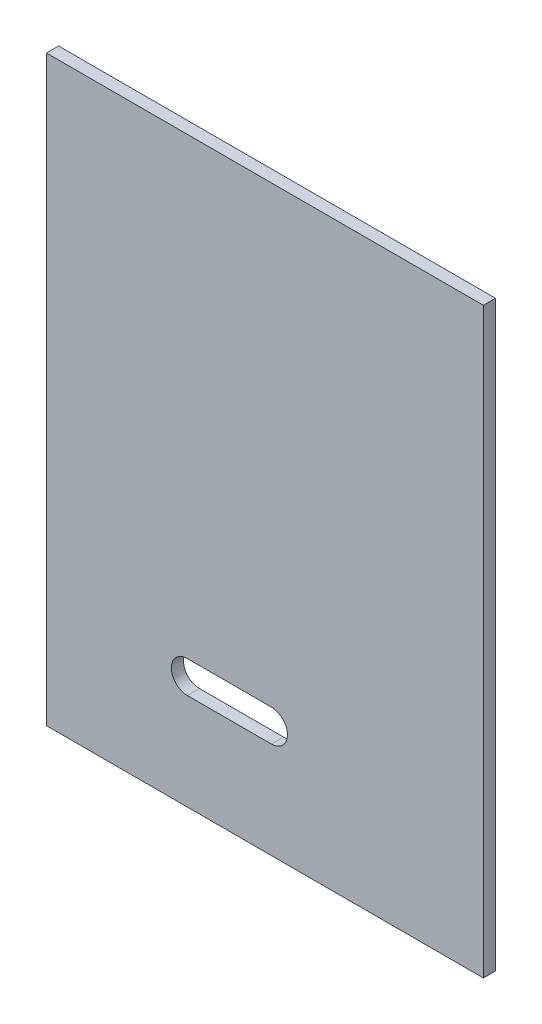
SolidWorks part; units mm, degrees
ref_plane "Front Plane" through (0, 0, 0) normal (0, 0, 1) x (1, 0, 0)
ref_plane "Top Plane" through (0, 0, 0) normal (0, 1, 0) x (1, 0, 0)
ref_plane "Right Plane" through (0, 0, 0) normal (1, 0, 0) x (0, 0, -1)
sketch "Sketch1" plane through (0, 0, 0) normal (0, 0, 1) x (1, 0, 0)
  line L0 (228.6, 0) -> (0, 0)
  line L1 (0, 0) -> (0, 304.8)
  line L2 (0, 304.8) -> (228.6, 304.8)
  line L3 (228.6, 304.8) -> (228.6, 0)
  dimension "D1" = 228.6
  dimension "D2" = 304.8
extrude "Boss-Extrude1" add sketch "Sketch1" along normal blind 6.35
sketch "Sketch2" plane through (0, 0, 6.35) normal (0, 0, 1) x (1, 0, 0)
  line L0 (73.7049, 58.9084) -> (117.7068, 58.9084) construction
  line L1 (73.7049, 67.2775) -> (117.7068, 67.2775)
  line L2 (73.7049, 50.5392) -> (117.7068, 50.5392)
  line L3 (0, 0) -> (228.6, 0) construction
  arc A0 (73.7049, 67.2775) -> (73.7049, 50.5392) centre (73.7049, 58.9084) ccw
  arc A1 (117.7068, 50.5392) -> (117.7068, 67.2775) centre (117.7068, 58.9084) ccw
  point P2 (95.7059, 58.9084)
extrude "Cut-Extrude1" cut sketch "Sketch2" against normal through all
